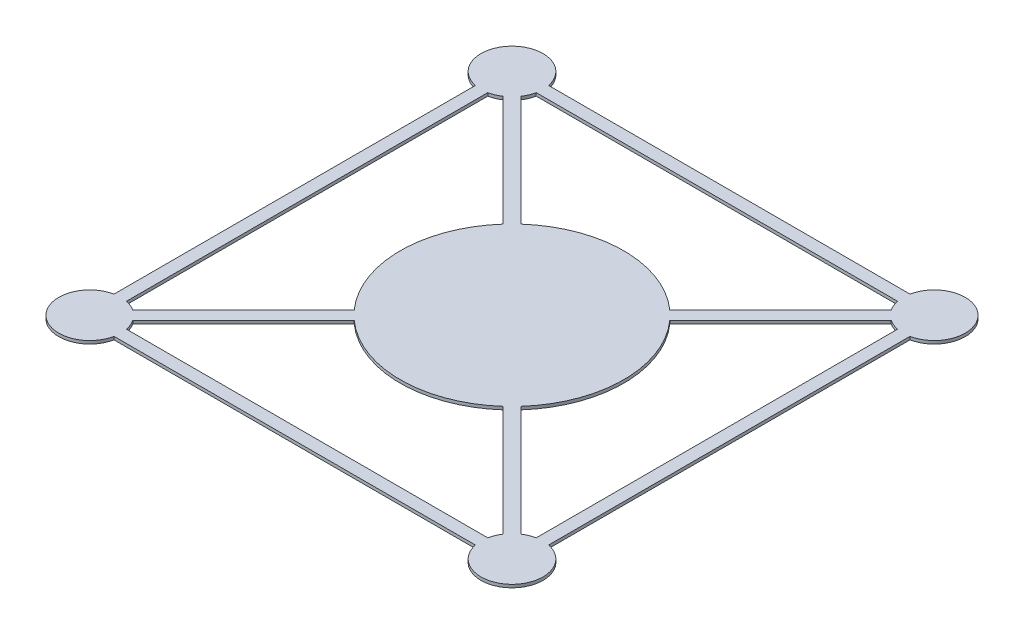
SolidWorks part; units mm, degrees
material "Thornel VCB-20 Carbon Cloth"
ref_plane "Front Plane" through (0, 0, 0) normal (0, 0, 1) x (1, 0, 0)
ref_plane "Top Plane" through (0, 0, 0) normal (0, 1, 0) x (1, 0, 0)
ref_plane "Right Plane" through (0, 0, 0) normal (1, 0, 0) x (0, 0, -1)
sketch "Sketch1" plane through (0, 0, 0) normal (0, 1, 0) x (1, 0, 0)
  line L0 (15.5543, 3.175) -> (200.3457, 3.175)
  line L1 (13.2436, 8.7535) -> (69.8463, 65.3562)
  line L2 (8.7535, 13.2436) -> (65.3562, 69.8463)
  line L3 (3.175, 15.5543) -> (3.175, 200.3457)
  line L4 (212.725, 15.5543) -> (212.725, 200.3457)
  line L5 (150.5438, 146.0537) -> (207.1465, 202.6564)
  line L7 (15.5543, 212.725) -> (200.3457, 212.725)
  line L10 (13.2436, 207.1465) -> (69.8463, 150.5438)
  line L11 (8.7535, 202.6564) -> (65.3562, 146.0537)
  line L15 (219.075, 15.5543) -> (219.075, 200.3457)
  line L16 (15.5543, 219.075) -> (200.3457, 219.075)
  line L19 (-3.175, 15.5543) -> (-3.175, 200.3457)
  line L21 (15.5543, -3.175) -> (200.3457, -3.175)
  line L22 (146.0537, 150.5438) -> (202.6564, 207.1465)
  line L33 (146.0537, 65.3562) -> (202.6564, 8.7535)
  line L35 (150.5438, 69.8463) -> (207.1465, 13.2436)
  arc A0 (200.3457, -3.175) -> (219.075, 15.5543) centre (215.9, 0) ccw
  arc A1 (15.5543, 219.075) -> (-3.175, 200.3457) centre (0, 215.9) ccw
  arc A2 (219.075, 200.3457) -> (200.3457, 219.075) centre (215.9, 215.9) ccw
  arc A3 (-3.175, 15.5543) -> (15.5543, -3.175) centre (0, 0) ccw
  arc A4 (8.7535, 13.2436) -> (3.175, 15.5543) centre (0, 0) ccw
  arc A5 (69.8463, 65.3562) -> (146.0537, 65.3562) centre (107.95, 107.95) ccw
  arc A6 (15.5543, 3.175) -> (13.2436, 8.7535) centre (0, 0) ccw
  arc A7 (150.5438, 69.8463) -> (150.5438, 146.0537) centre (107.95, 107.95) ccw
  arc A8 (146.0537, 150.5438) -> (69.8463, 150.5438) centre (107.95, 107.95) ccw
  arc A9 (65.3562, 146.0537) -> (65.3562, 69.8463) centre (107.95, 107.95) ccw
  arc A10 (202.6564, 8.7535) -> (200.3457, 3.175) centre (215.9, 0) ccw
  arc A11 (212.725, 15.5543) -> (207.1465, 13.2436) centre (215.9, 0) ccw
  arc A12 (207.1465, 202.6564) -> (212.725, 200.3457) centre (215.9, 215.9) ccw
  arc A13 (200.3457, 212.725) -> (202.6564, 207.1465) centre (215.9, 215.9) ccw
  arc A14 (3.175, 200.3457) -> (8.7535, 202.6564) centre (0, 215.9) ccw
  arc A15 (13.2436, 207.1465) -> (15.5543, 212.725) centre (0, 215.9) ccw
extrude "Boss-Extrude1" add sketch "Sketch1" along normal blind 1.5748
